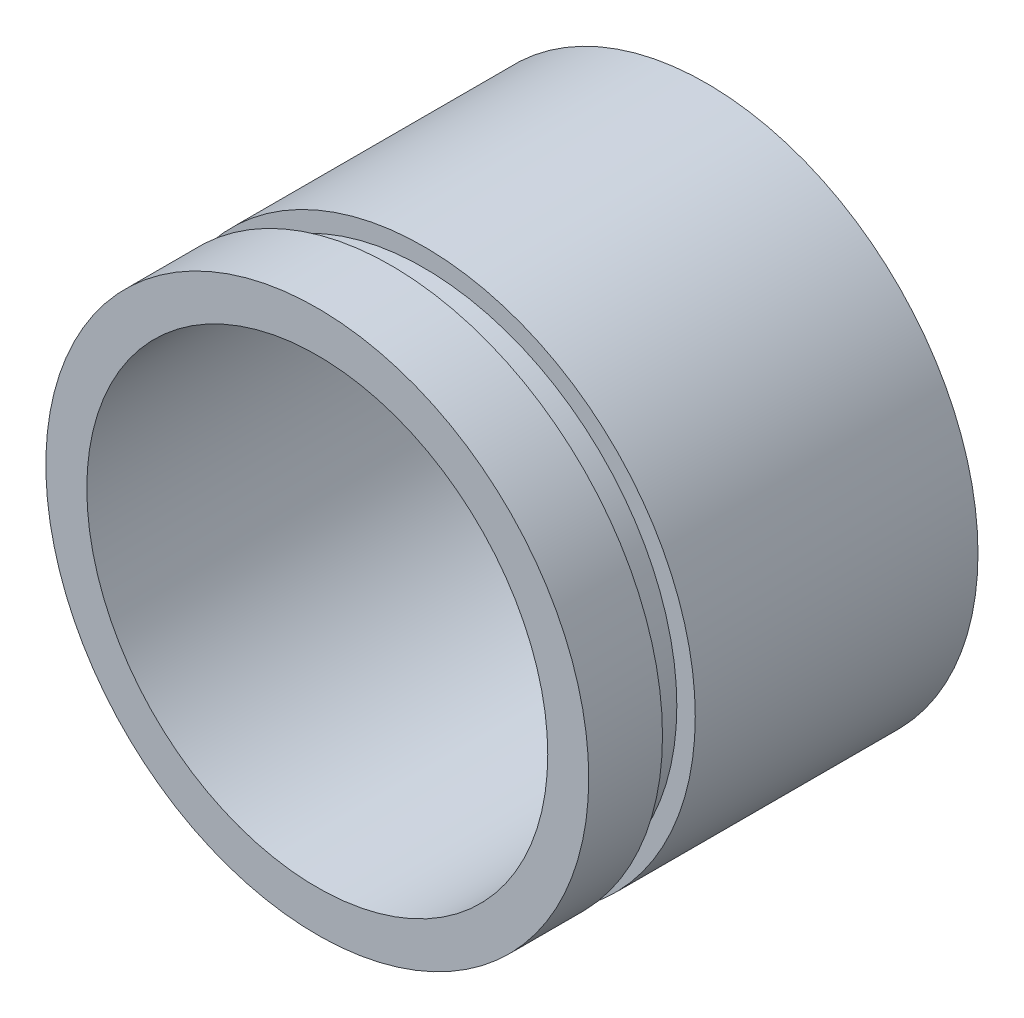
SolidWorks part; units mm, degrees
ref_plane "Front Plane" through (0, 0, 0) normal (0, 0, 1) x (1, 0, 0)
ref_plane "Top Plane" through (0, 0, 0) normal (0, 1, 0) x (1, 0, 0)
ref_plane "Right Plane" through (0, 0, 0) normal (1, 0, 0) x (0, 0, -1)
sketch "Sketch1" plane through (0, 0, 0) normal (0, 0, 1) x (1, 0, 0)
  circle A0 centre (0, 0) radius 26.5
  dimension "D1" = 53
extrude "Boss-Extrude1" add sketch "Sketch1" along normal mid plane 38
shell "Shell1" thickness 4
sketch "Sketch3" plane through (0, 0, 0) normal (0, 1, 0) x (1, 0, 0)
  line L0 (26.5, -19) -> (26.5, 19) construction
  line L1 (24.7, -11.8) -> (26.5, -11.8)
  line L2 (24.7, -11.8) -> (24.7, -8.6)
  line L3 (24.7, -8.6) -> (26.5, -8.6)
  line L4 (26.5, -11.8) -> (26.5, -8.6)
  dimension "D1" = 1.8
  dimension "D2" = 3.2
  dimension "D3" = 7.2
revolve "Cut-Revolve1" cut sketch "Sketch3" angle 360 about axis through (0, 0, 19) along (0, 0, -1)
